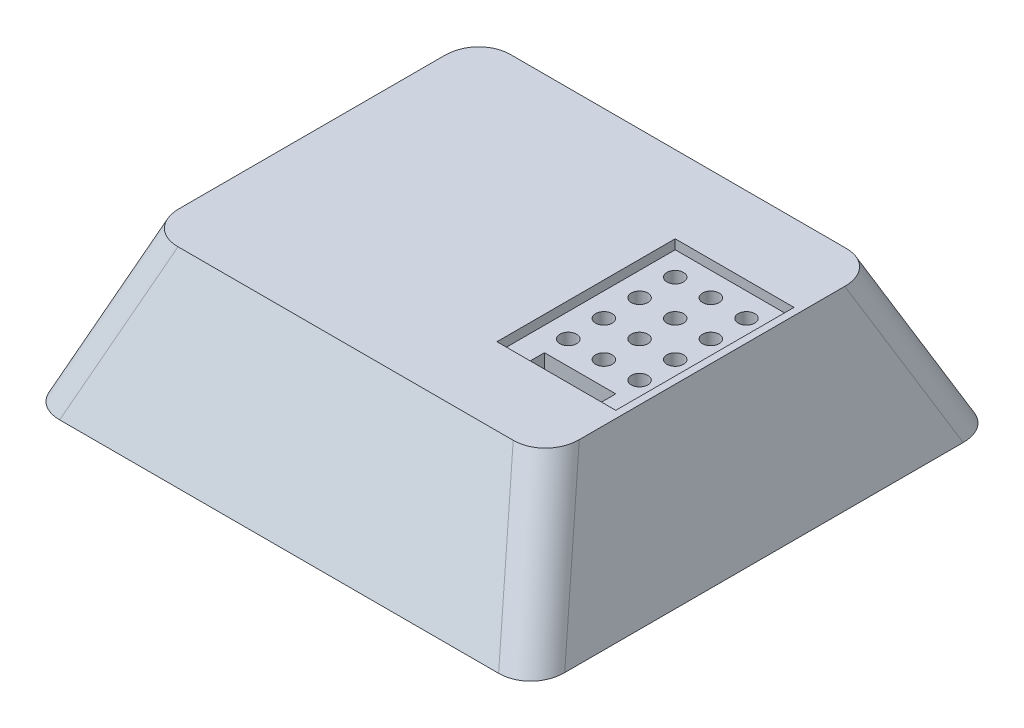
SolidWorks part; units mm, degrees
ref_plane "Front Plane" through (0, 0, 0) normal (0, 0, 1) x (1, 0, 0)
ref_plane "Top Plane" through (0, 0, 0) normal (0, 1, 0) x (1, 0, 0)
ref_plane "Right Plane" through (0, 0, 0) normal (1, 0, 0) x (0, 0, -1)
sketch "Master_Geometry" plane through (0, 0, 0) normal (0, 0, 1) x (1, 0, 0)
  line L0 (-48, -3.5) -> (-53, -3.5)
  line L1 (-47.5, -3.5) -> (47.5, -3.5) construction
  line L2 (-47.5, -3.5) -> (-47.5, 3.5) construction
  line L3 (-47.5, 3.5) -> (47.5, 3.5) construction
  line L4 (47.5, -3.5) -> (47.5, 3.5) construction
  line L5 (-47.5, -3.5) -> (47.5, 3.5) construction
  line L6 (-47.5, 3.5) -> (47.5, -3.5) construction
  line L7 (-53, -3.5) -> (-42.0809, 26.5)
  line L8 (-42.0809, 26.5) -> (42.0809, 26.5)
  line L13 (42.0809, 26.5) -> (53, -3.5)
  line L14 (53, -3.5) -> (48, -3.5)
  line L15 (48, -3.5) -> (48, 4)
  line L16 (48, 4) -> (43, 4)
  line L17 (43, 4) -> (43, 11.5)
  line L18 (39.3603, 21.5) -> (-39.3603, 21.5)
  line L19 (-43, 11.5) -> (-43, 4)
  line L20 (-43, 4) -> (-48, 4)
  line L21 (-48, 4) -> (-48, -3.5)
  line L22 (39.3603, 21.5) -> (43, 11.5)
  line L24 (-43, 11.5) -> (-39.3603, 21.5)
  point P0 (0, 0)
  dimension "D1" = 95
  dimension "D2" = 7
  dimension "D3" = 18
  dimension "D4" = 0.5
  dimension "D5" = 0.5
  dimension "D6" = 5
  dimension "D7" = 0.5
  dimension "D8" = 0.5
  dimension "D9" = 5
  dimension "D11" = 70
  dimension "D12" = 70
  dimension "D19" = 5
  dimension "D20" = 5
  dimension "D10" = 5
  dimension "D13" = 70
  dimension "D14" = 7.5
  dimension "D16" = 10
  dimension "D15" = 70
extrude "Top_Enclosure" add sketch "Master_Geometry" along normal blind 65
sketch "Sketch2" plane through (0, 0, 65) normal (0, 0, 1) x (1, 0, 0)
  line L0 (-42.0809, 26.5) -> (42.0809, 26.5)
  line L1 (42.0809, 26.5) -> (53, -3.5)
  line L2 (53, -3.5) -> (-53, -3.5)
  line L3 (-53, -3.5) -> (-42.0809, 26.5)
extrude "Top_Extra" add sketch "Sketch2" along normal blind 2.5
ref_plane "Plane_Symm" through (0, 0, 32.5) normal (0, 0, -1) x (-1, 0, 0)
mirror "Mirror1" about plane through (0, 0, 32.5) normal (0, 0, -1) of "Top_Extra"
sketch "Sketch3" plane through (0, 26.5, 0) normal (0, 1, 0) x (1, 0, 0)
  line L0 (13.75, -32.5) -> (-13.75, -32.5) construction
  line L1 (15.5809, -51.25) -> (40.5809, -51.25)
  line L2 (15.5809, -51.25) -> (15.5809, -13.75)
  line L3 (15.5809, -13.75) -> (40.5809, -13.75)
  line L4 (40.5809, -51.25) -> (40.5809, -13.75)
  line L5 (15.5809, -51.25) -> (40.5809, -13.75) construction
  line L6 (15.5809, -13.75) -> (40.5809, -51.25) construction
  line L7 (42.0809, -67.5) -> (42.0809, 2.5) construction
  point P0 (28.0809, -32.5)
  dimension "D1" = 25
  dimension "D2" = 37.5
  dimension "D3" = 1.5
extrude "Solar_Cell_Slot" cut sketch "Sketch3" against normal blind 2
sketch "Sketch5" plane through (0, 0, 0) normal (1, 0, 0) x (0, 0, -1)
  line L0 (-67.5, 26.5) -> (-67.5, -3.5)
  line L1 (-67.5, -3.5) -> (-81.4892, -3.5)
  line L2 (-81.4892, -3.5) -> (-67.5, 26.5)
  dimension "D1" = 65
extrude "Boss-Extrude1" add sketch "Sketch5" along normal up to surface (53 mm away)
sketch "Sketch6" plane through (0, 0, 0) normal (-1, 0, 0) x (0, 0, 1)
  line L0 (67.5, 26.5) -> (81.4892, -3.5)
  line L1 (81.4892, -3.5) -> (67.5, -3.5)
  line L2 (67.5, -3.5) -> (67.5, 26.5)
extrude "Boss-Extrude2" add sketch "Sketch6" along normal up to surface (42.0809 mm away) contours L2 L0 L1
mirror "Mirror3" about plane through (0, 0, 32.5) normal (0, 0, -1) of "Boss-Extrude2", "Boss-Extrude1"
fillet "Fillet1" radius 7.5 4 edges at (47.5404, 11.5, -9.4946) (-47.5404, 11.5, -9.4946) (47.5404, 11.5, 74.4946) (-47.5404, 11.5, 74.4946)
hole_wizard "CBORE for M5 Hex Head Bolt1" positions "Sketch7" profile "Sketch8" counterbore size "M5" standard "ANSI Metric"
sketch "Sketch7" plane through (0, -3.5, 0) normal (0, -1, 0) x (-1, 0, 0)
  line L0 (-46.1723, -81.4892) -> (46.1723, -81.4892) construction
  line L1 (-46.1723, 16.4892) -> (46.1723, 16.4892) construction
  point P0 (35, -69.4892)
  point P2 (0, -69.4892)
  point P4 (-35, -69.4892)
  point P6 (-35, 4.4892)
  point P8 (0, 4.4892)
  point P10 (35, 4.4892)
  dimension "D1" = 35
  dimension "D2" = 35
  dimension "D3" = 12
  dimension "D4" = 12
sketch "Sketch8" plane through (-35, -3.5, 69.4892) normal (1, 0, 0) x (0, 0, -1)
  line L0 (0, 0) -> (0, 10)
  line L1 (0, 10) -> (2.65, 10)
  line L2 (2.65, 10) -> (2.65, 5)
  line L3 (2.65, 5) -> (3.5, 5)
  line L4 (3.5, 5) -> (3.5, 0)
  line L5 (3.5, 0) -> (0, 0)
  line L10 (0, 10) -> (-2.65, 10) construction
  line L11 (0, -6.35) -> (0, 107.95) construction
  dimension "Hole Dia." = 5.3
  dimension "Hole Depth" = 10
  dimension "C'Bore Dia." = 7
  dimension "C'Bore Depth" = 5
  dimension "Drill Angle" = 180
sketch "Sketch9" plane through (0, 24.5, 0) normal (0, 1, 0) x (1, 0, 0)
  line L1 (15.5809, -13.75) -> (40.5809, -13.75)
  line L2 (15.5809, -13.75) -> (15.5809, -51.25)
  line L3 (15.5809, -51.25) -> (40.5809, -51.25)
  line L4 (40.5809, -13.75) -> (40.5809, -51.25)
sketch "Sketch10" plane through (0, 24.5, 0) normal (0, 1, 0) x (1, 0, 0)
  line L3 (15.5809, -13.75) -> (15.5809, -51.25) construction
  line L4 (40.5809, -13.75) -> (15.5809, -13.75) construction
  line L5 (15.5809, -51.25) -> (40.5809, -51.25) construction
  line L6 (20.5809, -51.25) -> (35.5809, -51.25)
  line L7 (20.5809, -51.25) -> (20.5809, -46.25)
  line L8 (20.5809, -46.25) -> (35.5809, -46.25)
  line L9 (35.5809, -51.25) -> (35.5809, -46.25)
  circle A0 centre (20.5809, -18.75) radius 1.75
  circle A1 centre (28.0809, -18.75) radius 1.75
  circle A2 centre (35.5809, -18.75) radius 1.75
  circle A3 centre (35.5809, -26.25) radius 1.75
  circle A4 centre (28.0809, -26.25) radius 1.75
  circle A5 centre (20.5809, -26.25) radius 1.75
  circle A6 centre (35.5809, -33.75) radius 1.75
  circle A7 centre (28.0809, -33.75) radius 1.75
  circle A8 centre (20.5809, -33.75) radius 1.75
  circle A9 centre (35.5809, -41.25) radius 1.75
  circle A10 centre (28.0809, -41.25) radius 1.75
  circle A11 centre (20.5809, -41.25) radius 1.75
  point P35 (28.0809, -51.25)
  point P36 (28.0809, -51.25)
  dimension "D1" = 3.5
  dimension "D2" = 3.5
  dimension "D3" = 3.5
  dimension "D4" = 12.5
  dimension "D5" = 7.5
  dimension "D6" = 7.5
  dimension "D7" = 5
  dimension "D9" = 15
  dimension "D10" = 12.5
  dimension "D11" = 5
  dimension "D8" = 4
extrude "Cut-Extrude1" cut sketch "Sketch10" against normal through all contours A5 | A4 | A3 | A9 | A10 | A11 | A8 | A7 | A6 | L7 L6 L9 L8 | A2 | A1 | A0
equation "\"rel_tol\"= 0.5mm"
equation "\"dist_pcb_top\"= 18mm"
equation "\"enclosure_angle\"= 70deg"
equation "\"solar_cell_x\"= 42mm"
equation "\"solar_cell_y\"= 35mm"
equation "\"solar_cell_z\"= 2mm"
equation "\"top_extra\"= 10mm"
equation "\"top_thickness\"= 5mm"
equation "\"top_extra_bottom\"= 5mm"
equation "\"solar_cell_pos\"= 35mm"
equation "\"bottom_overall_x\"= 95mm"
equation "\"bottom_overall_y\"= 7mm"
equation "\"D1@Master_Geometry\" = \"bottom_overall_x\""
equation "\"D3@Master_Geometry\" = \"dist_pcb_top\""
equation "\"D4@Master_Geometry\" = \"rel_tol\""
equation "\"D5@Master_Geometry\" = \"rel_tol\""
equation "\"D7@Master_Geometry\" = \"rel_tol\""
equation "\"D8@Master_Geometry\" = \"rel_tol\""
equation "\"D11@Master_Geometry\" = \"enclosure_angle\""
equation "\"D12@Master_Geometry\" = \"enclosure_angle\""
equation "\"D19@Master_Geometry\" = \"top_extra_bottom\""
equation "\"D20@Master_Geometry\" = \"top_extra_bottom\""
equation "\"pcb_length\"= 90mm"
equation "\"pcb_width\"= 65mm"
equation "\"D1@Top_Enclosure\"=65mm"
equation "\"D10@Master_Geometry\" = \"top_thickness\""
equation "\"top_extra_outside\"= 10mm"
equation "\"D1@Top_Extra\" = \"top_extra_outside\""
equation "\"D1@Solar_Cell_Slot\" = \"solar_cell_z\""
equation "\"flatter_region\"= 65deg"
equation "\"D1@Sketch5\"=\"flatter_region\""
